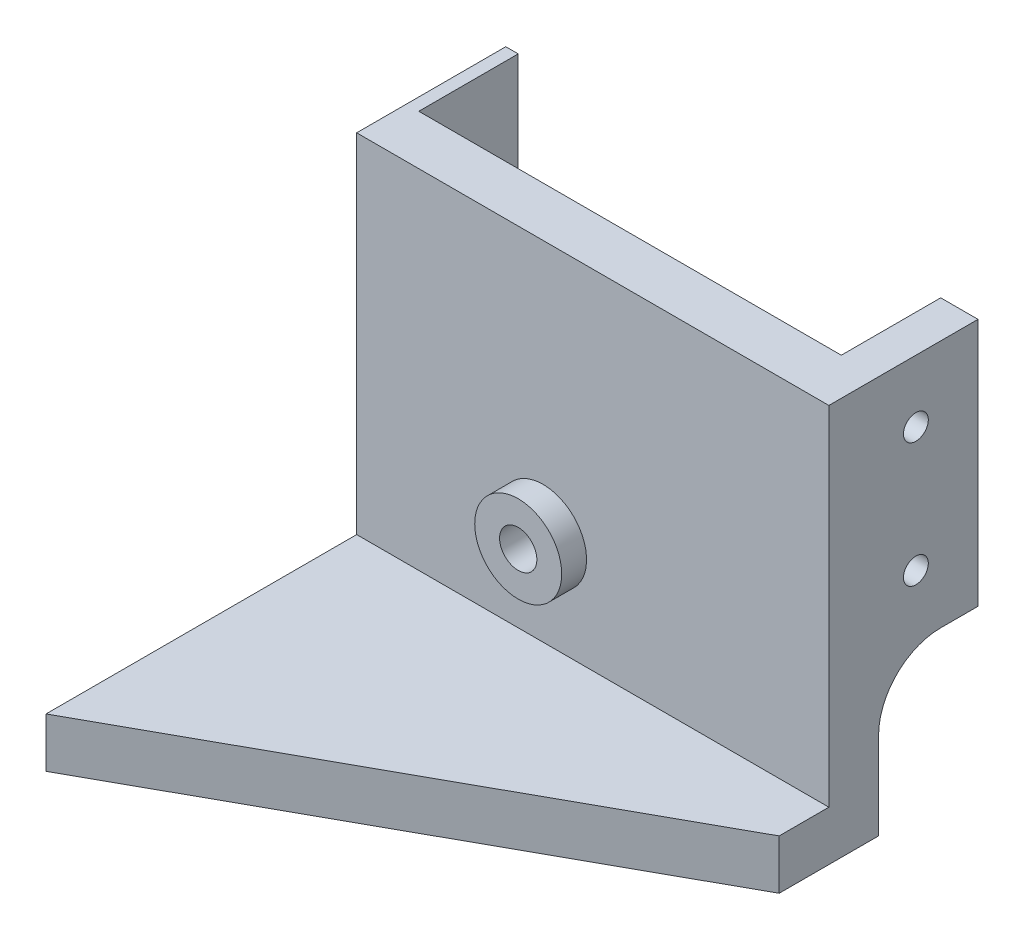
SolidWorks part; units mm, degrees
ref_plane "Front Plane" through (0, 0, 0) normal (0, 0, 1) x (1, 0, 0)
ref_plane "Top Plane" through (0, 0, 0) normal (0, 1, 0) x (1, 0, 0)
ref_plane "Right Plane" through (0, 0, 0) normal (1, 0, 0) x (0, 0, -1)
sketch "Sketch1" plane through (0, 0, 0) normal (0, 1, 0) x (1, 0, 0)
  line L1 (0, 0) -> (38, 0)
  line L2 (0, 0) -> (0, 12)
  line L3 (0, 12) -> (38, 12)
  line L4 (38, 0) -> (38, 12)
  line L5 (1, 12) -> (35, 12)
  line L6 (1, 12) -> (1, 4)
  line L7 (1, 4) -> (35, 4)
  line L8 (35, 12) -> (35, 4)
  dimension "D1" = 12
  dimension "D2" = 38
  dimension "D3" = 34
  dimension "D4" = 1
  dimension "10" = 8
extrude "Boss-Extrude1" add sketch "Sketch1" along normal blind 20 contours L3 L8 L7 L6 L2 L1 L4
sketch "Sketch2" plane through (0, 0, 0) normal (0, -1, 0) x (1, 0, 0)
  line L0 (38, 0) -> (38, -12) construction
  line L1 (0, 0) -> (38, 0)
  line L2 (0, 0) -> (0, -4)
  line L3 (0, -4) -> (38, -4)
  line L4 (38, 0) -> (38, -4)
extrude "Boss-Extrude2" add sketch "Sketch2" along normal blind 12
fillet "Fillet1" radius 5 2 edges at (0.5, 0, -4) (36.5, 0, -4)
sketch "Sketch3" plane through (0, 0, 0) normal (0, 0, 1) x (1, 0, 0)
  line L0 (38, 20) -> (38, -12) construction
  line L1 (0, -12) -> (38, -12)
  line L2 (0, -12) -> (0, -8)
  line L3 (0, -8) -> (38, -8)
  line L4 (38, -12) -> (38, -8)
  dimension "D1" = 4
extrude "Boss-Extrude3" add sketch "Sketch3" along normal blind 25 contours L3 L4 L1 L2
sketch "Sketch4" plane through (0, 0, 0) normal (0, 0, 1) x (1, 0, 0)
  line L0 (0, -8) -> (38, -8) construction
  line L1 (0, 20) -> (0, -8) construction
  circle A0 centre (15, -0.5) radius 1.5
  circle A1 centre (15, -0.5) radius 3.5
  dimension "D1" = 3
  dimension "D2" = 7.5
  dimension "D4" = 15
  dimension "D3" = 2
extrude "Boss-Extrude4" add sketch "Sketch4" along normal blind 2
sketch "Sketch5" plane through (0, 0, 2) normal (0, 0, 1) x (1, 0, 0)
  circle A0 centre (15, -0.5) radius 1.5 construction
  circle A1 centre (15, -0.5) radius 1.5
extrude "Cut-Extrude1" cut sketch "Sketch5" against normal through all contours A1
sketch "Sketch6" plane through (0, -8, 0) normal (0, 1, 0) x (1, 0, 0)
  line L0 (0, -25) -> (38, -4)
  line L1 (38, -25) -> (38, 0) construction
  line L2 (38, -4) -> (38, -25)
  line L3 (38, -25) -> (0, -25)
  dimension "D1" = 4
extrude "Cut-Extrude2" cut sketch "Sketch6" against normal blind 10
sketch "Sketch7" plane through (0, 0, 0) normal (-1, 0, 0) x (0, 0, 1)
  line L0 (-12, 20) -> (-12, 0) construction
  line L1 (0, 20) -> (-12, 20) construction
  line L2 (-9, 0) -> (-12, 0) construction
  circle A0 centre (-7, 15) radius 1
  circle A1 centre (-7, 5) radius 1
  point P6 (0, 0)
  dimension "D1" = 2
  dimension "D3" = 5
  dimension "D2" = 5
  dimension "D4" = 10
  dimension "D5" = 5
extrude "Cut-Extrude3" cut sketch "Sketch7" against normal through all both and the other way through all
